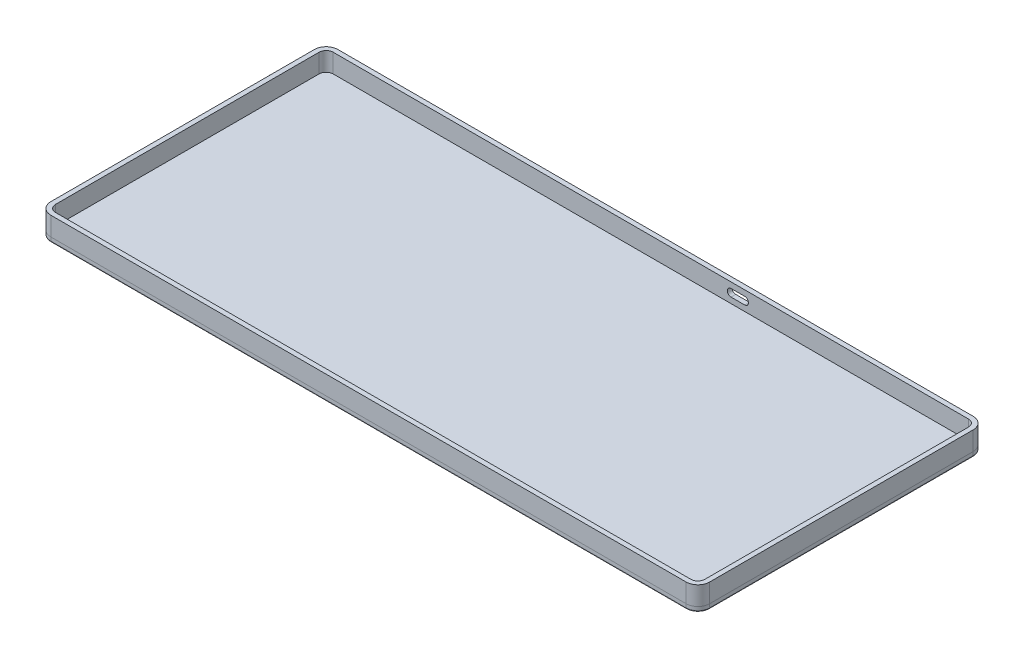
SolidWorks part; units mm, degrees
ref_plane "前视基准面" through (0, 0, 0) normal (0, 0, 1) x (1, 0, 0)
ref_plane "上视基准面" through (0, 0, 0) normal (0, 1, 0) x (1, 0, 0)
ref_plane "右视基准面" through (0, 0, 0) normal (1, 0, 0) x (0, 0, -1)
other "Configuration Table"
sketch "草图1" plane through (0, 0, 0) normal (0, 1, 0) x (1, 0, 0)
  line L1 (-135, 61) -> (135, 61)
  line L2 (-140, 56) -> (-140, -56)
  line L3 (-135, -61) -> (135, -61)
  line L4 (140, 56) -> (140, -56)
  line L5 (-140, 61) -> (140, -61) construction
  line L6 (-140, -61) -> (140, 61) construction
  arc A0 (135, 61) -> (140, 56) centre (135, 56) cw
  arc A1 (135, -61) -> (140, -56) centre (135, -56) ccw
  arc A2 (-140, -56) -> (-135, -61) centre (-135, -56) ccw
  arc A3 (-135, 61) -> (-140, 56) centre (-135, 56) ccw
  point P0 (0, 0)
  dimension "D3" = 5
  dimension "D1" = 122
  dimension "D2" = 280
extrude "凸台-拉伸1" add sketch "草图1" along normal blind 2
sketch "草图2" plane through (0, 2, 0) normal (0, 1, 0) x (1, 0, 0)
  line L24 (135, 59) -> (-135, 59)
  line L25 (-138, 56) -> (-138, -56)
  line L26 (-135, -59) -> (135, -59)
  line L27 (138, -56) -> (138, 56)
  line L28 (135, 61) -> (-135, 61)
  line L29 (-140, 56) -> (-140, -56)
  line L30 (-135, -61) -> (135, -61)
  line L31 (140, -56) -> (140, 56)
  line L32 (135, 61) -> (-135, 61)
  line L33 (-140, 56) -> (-140, -56)
  line L34 (-135, -61) -> (135, -61)
  line L35 (140, -56) -> (140, 56)
  arc A8 (-135, 59) -> (-138, 56) centre (-135, 56) ccw
  arc A9 (-138, -56) -> (-135, -59) centre (-135, -56) ccw
  arc A10 (135, -59) -> (138, -56) centre (135, -56) ccw
  arc A11 (138, 56) -> (135, 59) centre (135, 56) ccw
  arc A12 (140, 56) -> (135, 61) centre (135, 56) ccw
  arc A13 (-135, 61) -> (-140, 56) centre (-135, 56) ccw
  arc A14 (-140, -56) -> (-135, -61) centre (-135, -56) ccw
  arc A15 (135, -61) -> (140, -56) centre (135, -56) ccw
  arc A16 (140, 56) -> (135, 61) centre (135, 56) ccw
  arc A17 (-135, 61) -> (-140, 56) centre (-135, 56) ccw
  arc A18 (-140, -56) -> (-135, -61) centre (-135, -56) ccw
  arc A19 (135, -61) -> (140, -56) centre (135, -56) ccw
  dimension "D2" = 2
  dimension "D1" = 0
extrude "凸台-拉伸2" add sketch "草图2" along normal blind 8 separate body
sketch "草图3" plane through (0, 0, -61) normal (0, 0, -1) x (-1, 0, 0)
  line L0 (-140, 10) -> (-42, 10) construction
  line L1 (-135, 10) -> (135, 10) construction
  line L3 (-42, 10) -> (-42, 4) construction
  line L5 (-42, 4) -> (-32, 4) construction
  line L8 (-32, 4) -> (-32, 10) construction
  line L10 (-32, 10) -> (-42, 10) construction
  line L11 (-37, 4) -> (-37, 18.7802) construction
  line L12 (-32, 10) -> (-32, 6) construction
  line L13 (-32, 6) -> (-42, 6) construction
  line L14 (-34.085, 7.585) -> (-34.085, 4) construction
  line L15 (-41.5, 7.585) -> (-32.5, 7.585) construction
  line L16 (-41.5, 7.585) -> (-41.5, 4.415) construction
  line L17 (-41.5, 4.415) -> (-32.5, 4.415) construction
  line L18 (-32.5, 7.585) -> (-32.5, 4.415) construction
  line L19 (-41.5, 7.585) -> (-32.5, 4.415) construction
  line L20 (-41.5, 4.415) -> (-32.5, 7.585) construction
  line L21 (-39.915, 7.585) -> (-34.085, 7.585)
  line L22 (-34.085, 4.415) -> (-39.915, 4.415)
  arc A0 (-34.085, 7.585) -> (-34.085, 4.415) centre (-34.085, 6) cw
  arc A1 (-39.915, 7.585) -> (-39.915, 4.415) centre (-39.915, 6) ccw
  point P12 (-37, 6)
  dimension "D1" = 98
  dimension "D2" = 10
  dimension "D3" = 6
  dimension "D4" = 4
  dimension "D5" = 3.17
  dimension "D6" = 9
extrude "切除-拉伸7" cut sketch "草图3" against normal up to next (2 mm away)
sketch "草图4" plane through (0, 2, 0) normal (0, 1, 0) x (1, 0, 0)
  line L8 (0, 0) -> (0, 179.642) construction
  line L9 (135, 59) -> (-135, 59) construction
  line L10 (138, -56) -> (138, 56) construction
  line L11 (-135, -59) -> (135, -59) construction
  circle A8 centre (94, 42.5) radius 2
  circle A9 centre (111, 3) radius 2
  circle A10 centre (117, -49) radius 2
  circle A11 centre (18, -3) radius 2
  circle A12 centre (94, 42.5) radius 3.15
  circle A13 centre (111, 3) radius 3.15
  circle A14 centre (117, -49) radius 3.15
  circle A15 centre (18, -3) radius 3.15
  circle A16 centre (-18, -3) radius 3.15
  circle A17 centre (-117, -49) radius 3.15
  circle A18 centre (-111, 3) radius 3.15
  circle A19 centre (-94, 42.5) radius 3.15
  circle A20 centre (-18, -3) radius 2
  circle A21 centre (-117, -49) radius 2
  circle A22 centre (-111, 3) radius 2
  circle A23 centre (-94, 42.5) radius 2
  dimension "D4" = 27
  dimension "D7" = 21
  dimension "D1" = 4
  dimension "D2" = 16.5
  dimension "D8" = 56
  dimension "D9" = 120
  dimension "D3" = 44
  dimension "D5" = 56
  dimension "D6" = 10
  dimension "D10" = 1.15
sketch "草图7" plane through (0, 2, 0) normal (0, 1, 0) x (1, 0, 0)
  line L0 (32.5, 60) -> (41.5, 60) construction
  line L1 (32.5, 61) -> (32.5, 59) construction
  line L2 (41.5, 59) -> (41.5, 61) construction
  line L3 (41.5, 61) -> (41.5, 54.5) construction
  line L4 (135, 61) -> (-135, 61) construction
  line L5 (41.5, 54.5) -> (32.5, 54.5)
  line L6 (32.5, 54.5) -> (32.5, 53)
  line L7 (32.5, 53) -> (41.5, 53)
  line L8 (41.5, 53) -> (41.5, 54.5)
  line L9 (37, 60) -> (37, 46.6181) construction
  line L10 (41.5, 55.5) -> (41.5, 54.5)
  line L11 (41.5, 55.5) -> (40.5, 55.5)
  line L12 (40.5, 55.5) -> (40.5, 54.5)
  line L13 (41.5, 55.5) -> (41.5, 54.5)
  line L14 (41.5, 54.5) -> (40.5, 54.5)
  line L15 (32.5, 54.5) -> (33.5, 54.5)
  line L16 (32.5, 55.5) -> (32.5, 54.5)
  line L17 (33.5, 55.5) -> (33.5, 54.5)
  line L18 (32.5, 55.5) -> (33.5, 55.5)
  line L19 (32.5, 55.5) -> (32.5, 54.5)
  line L20 (135, 59) -> (-135, 59) construction
  line L21 (33.5, 54.5) -> (40.5, 54.5)
  line L22 (33.5, 54.5) -> (33.5, 59)
  line L23 (33.5, 59) -> (40.5, 59)
  line L24 (40.5, 54.5) -> (40.5, 59)
  point P17 (37, 60)
  dimension "D1" = 6.5
  dimension "D2" = 1.5
  dimension "D3" = 9
  dimension "D4" = 1
  dimension "D5" = 1
fillet "圆角1" radius 0.5 8 edges at (0, 0, -61) (-138.5355, 0, -59.5355) (-140, 0, 0) (-138.5355, 0, 59.5355) (0, 0, 61) (138.5355, 0, 59.5355) (140, 0, 0) (138.5355, 0, -59.5355)
sketch "草图8" plane through (0, 0, 0) normal (0, -1, 0) x (1, 0, 0)
  line L0 (0, 60.5) -> (0, -60.5) construction
  line L1 (135, 60.5) -> (-135, 60.5) construction
  line L2 (-135, -60.5) -> (135, -60.5) construction
  line L3 (139.5, -56) -> (139.5, 56) construction
  line L4 (87.5, 48.5) -> (119.5, 48.5)
  line L5 (87.5, 48.5) -> (87.5, 36.5)
  line L6 (87.5, 36.5) -> (119.5, 36.5)
  line L7 (119.5, 48.5) -> (119.5, 36.5)
  line L8 (-99.5, -44.5) -> (-99.5, -50.5)
  line L9 (74.5, -44.5) -> (99.5, -44.5)
  line L10 (74.5, -44.5) -> (74.5, -50.5)
  line L11 (74.5, -50.5) -> (99.5, -50.5)
  line L12 (99.5, -44.5) -> (99.5, -50.5)
  line L13 (-25, 10) -> (25, 10)
  line L14 (-25, 10) -> (-25, -10)
  line L15 (-25, -10) -> (25, -10)
  line L16 (25, 10) -> (25, -10)
  line L17 (-25, 10) -> (25, -10) construction
  line L18 (-25, -10) -> (25, 10) construction
  line L19 (-74.5, -50.5) -> (-99.5, -50.5)
  line L20 (-74.5, -44.5) -> (-74.5, -50.5)
  line L21 (-74.5, -44.5) -> (-99.5, -44.5)
  line L22 (-119.5, 48.5) -> (-119.5, 36.5)
  line L23 (-87.5, 36.5) -> (-119.5, 36.5)
  line L24 (-87.5, 48.5) -> (-87.5, 36.5)
  line L25 (-87.5, 48.5) -> (-119.5, 48.5)
  point P16 (0, 0)
  dimension "D1" = 12
  dimension "D2" = 32
  dimension "D3" = 12
  dimension "D4" = 20
  dimension "D5" = 6
  dimension "D6" = 25
  dimension "D7" = 10
  dimension "D8" = 40
  dimension "D9" = 20
  dimension "D10" = 50
